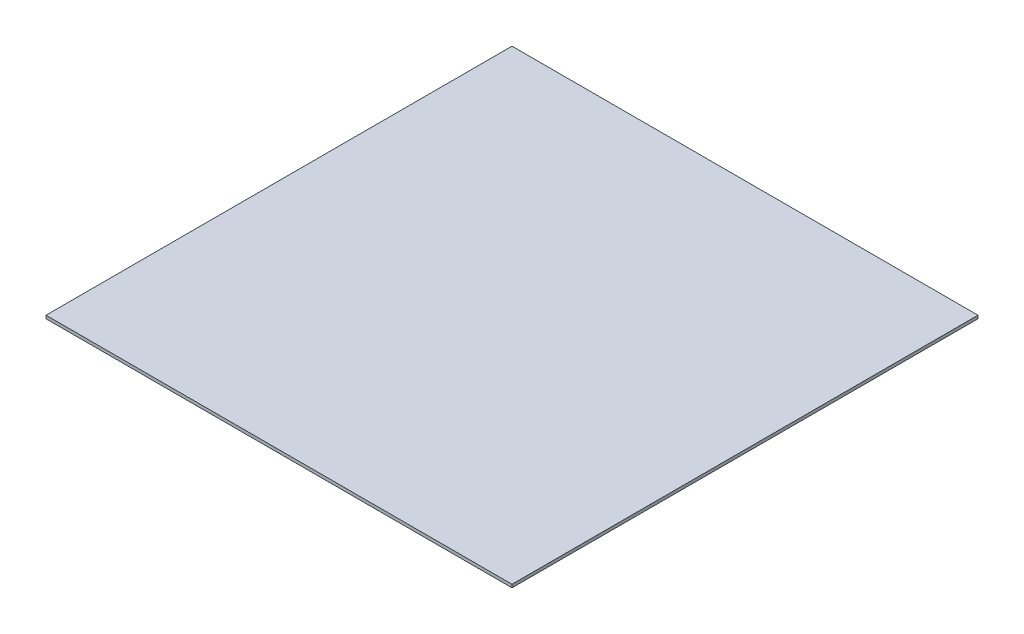
SolidWorks part; units mm, degrees
ref_plane "Front" through (0, 0, 0) normal (0, 0, 1) x (1, 0, 0)
ref_plane "Top" through (0, 0, 0) normal (0, 1, 0) x (1, 0, 0)
ref_plane "Right" through (0, 0, 0) normal (1, 0, 0) x (0, 0, -1)
sketch "Sketch1" plane through (0, 0, 0) normal (0, 1, 0) x (1, 0, 0)
  line L1 (0, 0) -> (300, 0)
  line L2 (0, 0) -> (0, 300)
  line L3 (0, 300) -> (300, 300)
  line L4 (300, 0) -> (300, 300)
  dimension "D1" = 300
  dimension "D2" = 300
extrude "Boss-Extrude1" add sketch "Sketch1" along normal blind 2
sketch "Sketch2" plane through (0, 0, 0) normal (0, -1, 0) x (1, 0, 0)
  line L0 (0, 0) -> (300, -300) construction
  line L1 (300, 0) -> (0, -300) construction
  line L2 (150, -300) -> (150, 0) construction
  line L3 (300, -300) -> (0, -300) construction
  line L4 (0, 0) -> (300, 0) construction
sketch "Sketch3" plane through (0, 2, 0) normal (0, 1, 0) x (1, 0, 0)
  line L0 (0, 150) -> (300, 150) construction
  line L1 (0, 300) -> (0, 0) construction
  line L2 (300, 0) -> (300, 300) construction
